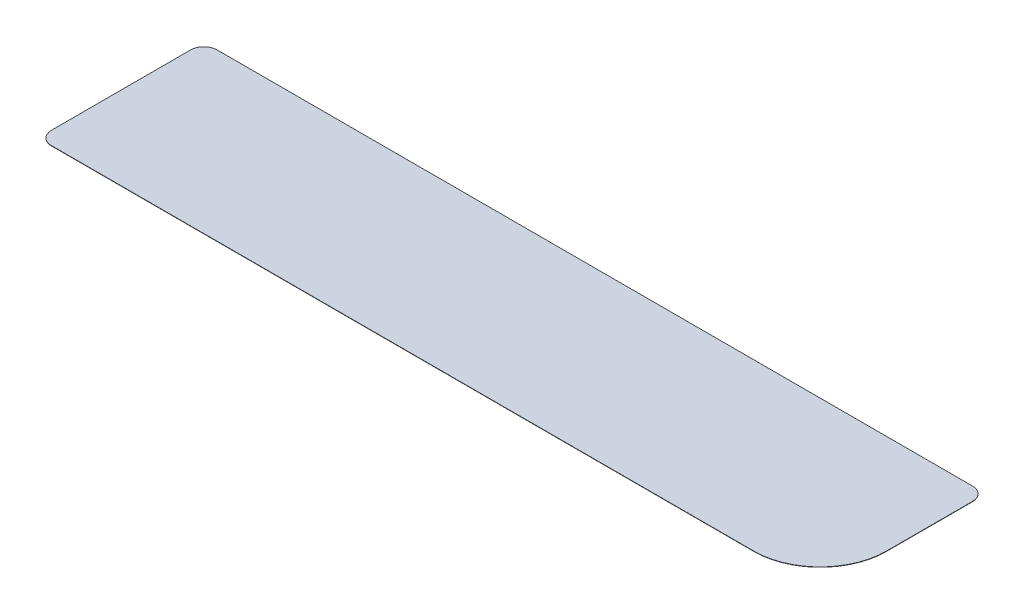
SolidWorks part; units mm, degrees
ref_plane "Front Plane" through (0, 0, 0) normal (0, 0, 1) x (1, 0, 0)
ref_plane "Top Plane" through (0, 0, 0) normal (0, 1, 0) x (1, 0, 0)
ref_plane "Right Plane" through (0, 0, 0) normal (1, 0, 0) x (0, 0, -1)
sketch "Sketch1" plane through (0, 0, 0) normal (0, 1, 0) x (1, 0, 0)
  line L1 (2, 12.5) -> (116, 12.5)
  line L2 (0, 10.5) -> (0, -10.5)
  line L3 (2, -12.5) -> (108, -12.5)
  line L4 (118, 10.5) -> (118, -2.5)
  arc A0 (116, 12.5) -> (118, 10.5) centre (116, 10.5) cw
  arc A1 (0, 10.5) -> (2, 12.5) centre (2, 10.5) cw
  arc A2 (2, -12.5) -> (0, -10.5) centre (2, -10.5) cw
  arc A3 (118, -2.5) -> (108, -12.5) centre (108, -2.5) cw
  point P4 (0, 0)
  point P8 (118, 12.5)
  point P11 (0, 12.5)
  point P14 (0, -12.5)
  dimension "D3" = 2
  dimension "D4" = 10
  dimension "D1" = 25
  dimension "D2" = 118
extrude "Boss-Extrude1" add sketch "Sketch1" along normal blind 0.05
